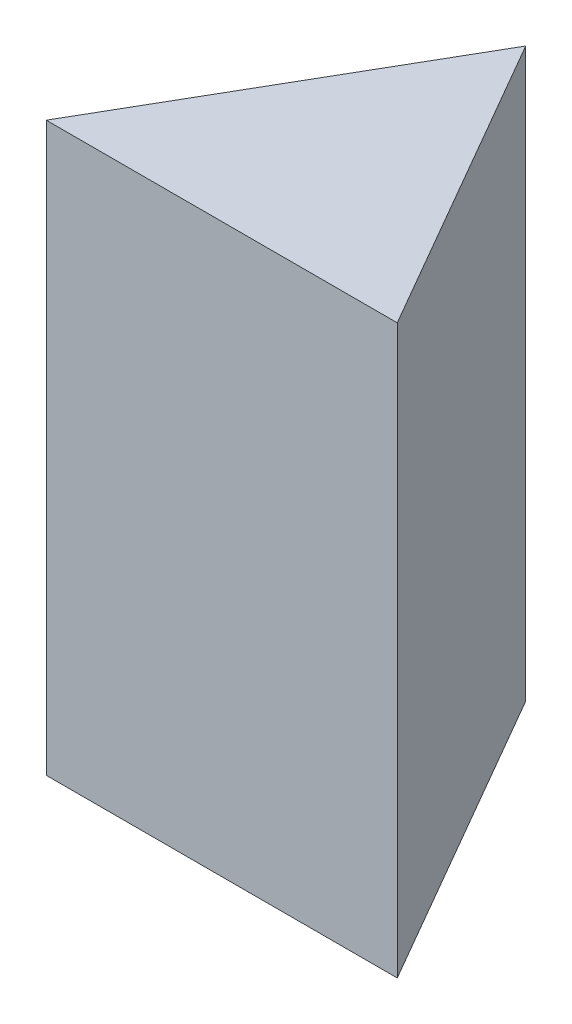
SolidWorks part; units mm, degrees
ref_plane "前视基准面" through (0, 0, 0) normal (0, 0, 1) x (1, 0, 0)
ref_plane "上视基准面" through (0, 0, 0) normal (0, 1, 0) x (1, 0, 0)
ref_plane "右视基准面" through (0, 0, 0) normal (1, 0, 0) x (0, 0, -1)
other "Configuration Table"
sketch "草图1" plane through (0, 0, 0) normal (0, 1, 0) x (1, 0, 0)
  line L0 (0, 25) -> (21.6506, -12.5)
  line L1 (21.6506, -12.5) -> (-21.6506, -12.5)
  line L2 (-21.6506, -12.5) -> (0, 25)
  line L3 (-16.4545, -9.5) -> (0, 19)
  line L4 (0, 19) -> (16.4545, -9.5)
  line L5 (16.4545, -9.5) -> (-16.4545, -9.5)
  circle A0 centre (0, 0) radius 25 construction
  dimension "D1" = 50
  dimension "D2" = 60
  dimension "D3" = 3
extrude "凸台-拉伸1" add sketch "草图1" along normal blind 70
sketch "草图2" plane through (0, 70, 0) normal (0, 1, 0) x (1, 0, 0)
  line L0 (0, 19) -> (16.4545, -9.5)
  line L1 (0, 19) -> (-16.4545, -9.5) construction
  line L2 (16.4545, -9.5) -> (0, 19) construction
  line L9 (16.4545, -9.5) -> (-16.4545, -9.5)
  line L10 (-16.4545, -9.5) -> (0, 19)
extrude "凸台-拉伸2" add sketch "草图2" against normal blind 5
sketch "草图3" plane through (0, 0, 0) normal (0, -1, 0) x (1, 0, 0)
  line L0 (-16.4545, 9.5) -> (16.4545, 9.5)
  line L1 (16.4545, 9.5) -> (0, -19)
  line L2 (0, -19) -> (-16.4545, 9.5)
  line L3 (0, -9) -> (-7.7942, 4.5)
  line L4 (-7.7942, 4.5) -> (7.7942, 4.5)
  line L5 (7.7942, 4.5) -> (0, -9)
  dimension "D1" = 5
extrude "凸台-拉伸3" add sketch "草图3" against normal blind 5
